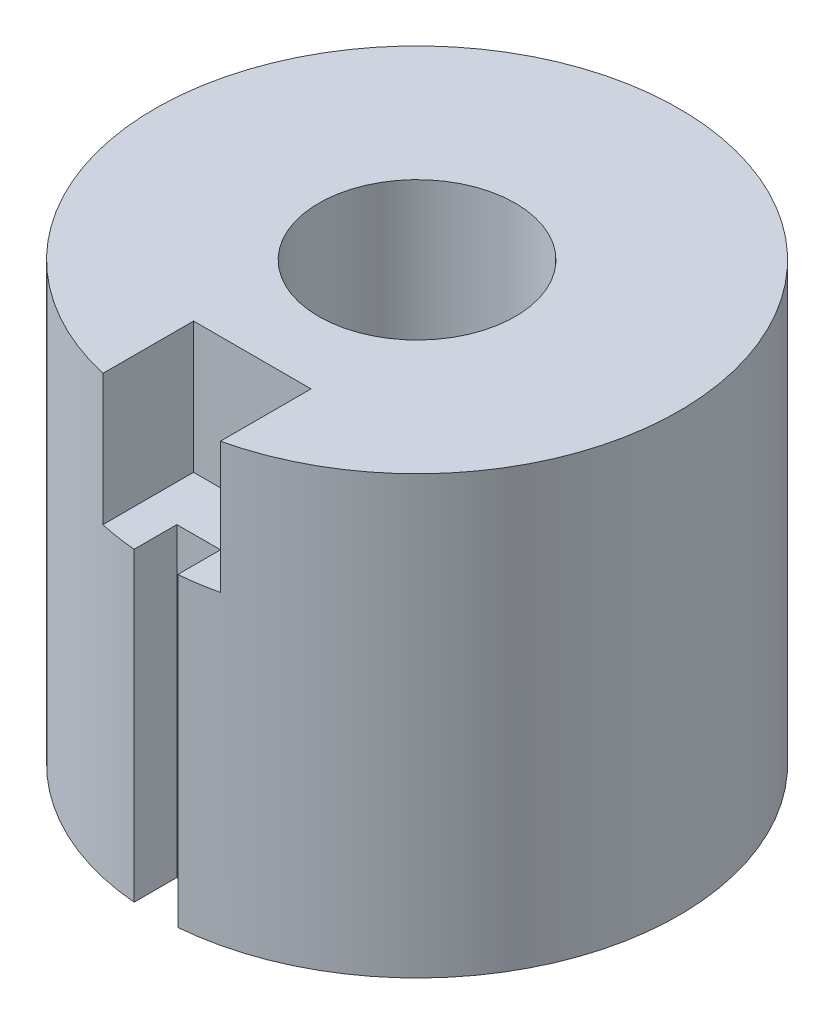
SolidWorks part; units mm, degrees
ref_plane "Plan de face" through (0, 0, 0) normal (0, 0, 1) x (1, 0, 0)
ref_plane "Plan de dessus" through (0, 0, 0) normal (0, 1, 0) x (1, 0, 0)
ref_plane "Plan de droite" through (0, 0, 0) normal (1, 0, 0) x (0, 0, -1)
sketch "Esquisse1" plane through (0, 0, 0) normal (0, 1, 0) x (1, 0, 0)
  circle A0 centre (0, 0) radius 2.25
  circle A1 centre (0, 0) radius 6
  dimension "D1" = 4.5
  dimension "D2" = 12
extrude "Boss.-Extru.1" add sketch "Esquisse1" along normal blind 10
sketch "Esquisse2" plane through (0, 10, 0) normal (0, 1, 0) x (1, 0, 0)
  line L0 (0, 0) -> (0, -6) construction
  line L1 (0.5, -6) -> (0.5, -5) construction
  line L2 (-0.5, -7) -> (0.5, -7)
  line L3 (-0.5, -7) -> (-0.5, -5)
  line L4 (-0.5, -5) -> (0.5, -5)
  line L5 (0.5, -7) -> (0.5, -5)
  line L6 (-0.5, -7) -> (0.5, -5) construction
  line L7 (-0.5, -5) -> (0.5, -7) construction
  circle A0 centre (0, 0) radius 6 construction
  dimension "D1" = 1
  dimension "D2" = 1
extrude "Enlèv. mat.-Extru.1" cut sketch "Esquisse2" against normal blind 20
sketch "Esquisse3" plane through (0, 10, 0) normal (0, 1, 0) x (1, 0, 0)
  line L0 (0, -5) -> (0, 0) construction
  line L1 (0.5, -5) -> (-0.5, -5) construction
  line L3 (1.3453, -6.2275) -> (-1.3453, -6.2275)
  line L4 (1.3453, -6.2275) -> (1.3453, -3.7725)
  line L5 (1.3453, -3.7725) -> (-1.3453, -3.7725)
  line L6 (-1.3453, -6.2275) -> (-1.3453, -3.7725)
  line L7 (1.3453, -6.2275) -> (-1.3453, -3.7725) construction
  line L8 (1.3453, -3.7725) -> (-1.3453, -6.2275) construction
extrude "Enlèv. mat.-Extru.2" cut sketch "Esquisse3" against normal blind 3
